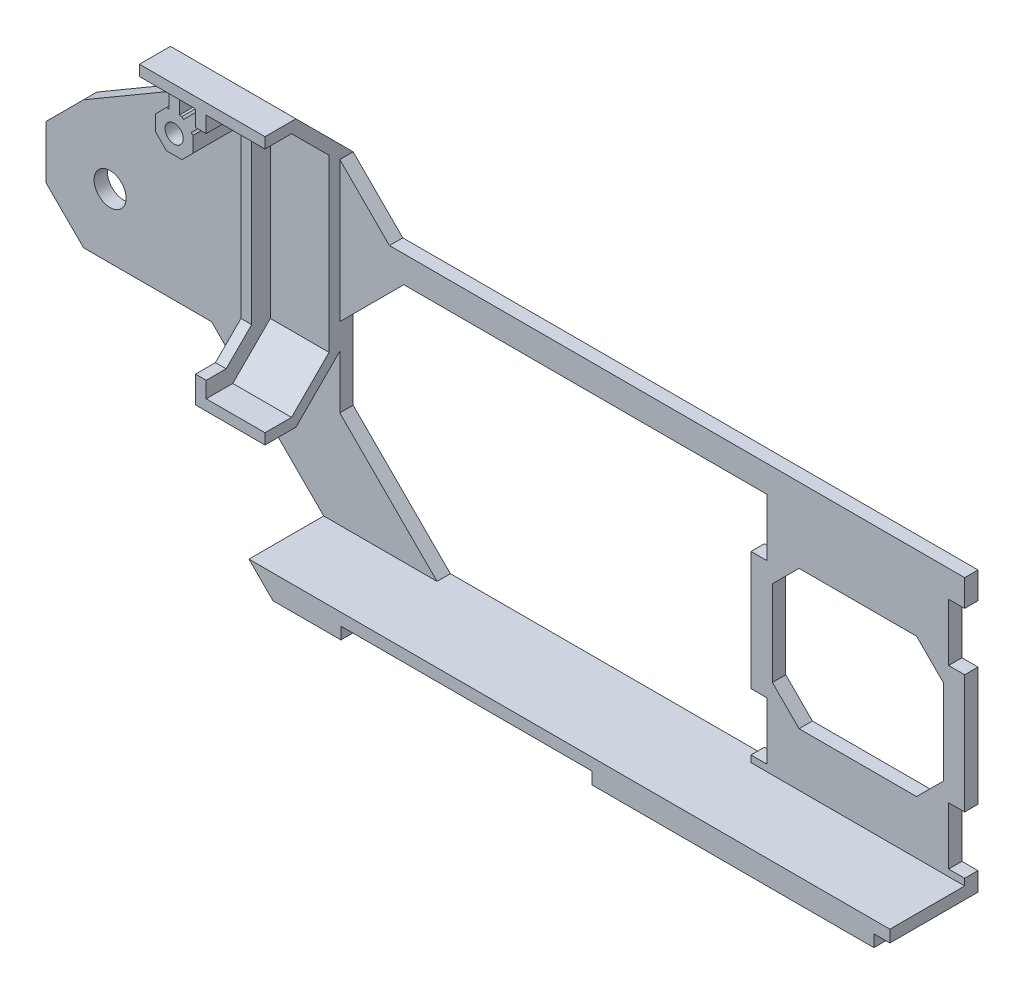
SolidWorks part; units mm, degrees
ref_plane "Front Plane" through (0, 0, 0) normal (0, 0, 1) x (1, 0, 0)
ref_plane "Top Plane" through (0, 0, 0) normal (0, 1, 0) x (1, 0, 0)
ref_plane "Right Plane" through (0, 0, 0) normal (1, 0, 0) x (0, 0, -1)
sketch "Sketch1" plane through (0, 0, 0) normal (0, 0, 1) x (1, 0, 0)
  line L0 (20, 0) -> (-100, 0) construction
  line L1 (0, 33) -> (-140, 33) construction
  line L3 (20, 45) -> (20, -2.25)
  line L5 (-121, 21) -> (-95.5, -4.5)
  line L6 (-17, 45) -> (20, 45) construction
  line L7 (17, -4.5) -> (-95.5, -4.5)
  line L9 (-78.7868, 0) -> (-20, 0)
  line L10 (-20, 0) -> (-20, 34.25)
  line L12 (20, 0) -> (-20, 0) construction
  line L13 (20, -4.5) -> (-100, -4.5) construction
  line L16 (20, -2.25) -> (17, -2.25)
  line L17 (17, -2.25) -> (17, -4.5)
  line L18 (-17, 45) -> (-85, 45)
  line L19 (0, 0) -> (0, 60) construction
  line L22 (16, 45) -> (16, -2.25) construction
  line L23 (0, 33) -> (20, 33) construction
  line L24 (-16, 45) -> (-16, -4.5) construction
  line L25 (20, 45) -> (20, 50)
  line L29 (-144.9706, 45) -> (-139.9706, 50)
  line L34 (20, 50) -> (-97, 50)
  line L41 (-108, 33) -> (-108, 60.9497) construction
  line L42 (11, 36) -> (-11, 36)
  line L43 (-11, 36) -> (-16, 31)
  line L44 (-16, 31) -> (-16, 15)
  line L45 (-16, 15) -> (-11, 10)
  line L46 (-11, 10) -> (11, 10)
  line L47 (11, 10) -> (16, 15)
  line L48 (16, 15) -> (16, 31)
  line L49 (16, 31) -> (11, 36)
  line L50 (-117, 33) -> (-117, 59) construction
  line L52 (-113.5, 57.5503) -> (-113.5, 60.4497)
  line L53 (-113.5, 60.4497) -> (-115.5503, 62.5)
  line L54 (-115.5503, 62.5) -> (-118.4497, 62.5)
  line L55 (-118.4497, 62.5) -> (-120.5, 60.4497)
  line L56 (-120.5, 60.4497) -> (-120.5, 57.5503)
  line L57 (-120.5, 57.5503) -> (-118.4497, 55.5)
  line L58 (-118.4497, 55.5) -> (-115.5503, 55.5)
  line L59 (-115.5503, 55.5) -> (-113.5, 57.5503)
  line L60 (-135.0294, 21) -> (-121, 21)
  line L61 (-135.0294, 45) -> (-144.9706, 45)
  line L62 (-144.9706, 45) -> (-152, 37.9706)
  line L63 (-152, 37.9706) -> (-152, 28.0294)
  line L64 (-152, 28.0294) -> (-144.9706, 21)
  line L65 (-144.9706, 21) -> (-135.0294, 21)
  line L66 (-135.0294, 21) -> (-128, 28.0294)
  line L67 (-128, 28.0294) -> (-128, 37.9706)
  line L68 (-128, 37.9706) -> (-135.0294, 45)
  line L73 (-152, 37.9706) -> (-152, 38.0503)
  line L75 (-97, 33) -> (-97, 50) construction
  line L76 (-78.7868, 0) -> (-97, 18.2132)
  line L78 (-135.0294, 45) -> (-123.7868, 45) construction
  line L79 (-123.7868, 45) -> (-97, 18.2132) construction
  line L81 (-82.7868, 0) -> (-82.7868, -4.5) construction
  line L82 (-35.7868, 0) -> (-35.7868, -4.5) construction
  line L83 (-82.7868, -2.25) -> (-35.7868, -2.25) construction
  line L84 (20, 1.25) -> (17, 1.25)
  line L85 (17, 1.25) -> (17, 12)
  line L86 (17, 12) -> (20, 12)
  line L87 (-20, 12) -> (-17, 12)
  line L88 (-17, 12) -> (-17, 1.25)
  line L89 (-17, 1.25) -> (-20, 1.25)
  line L90 (20, 34.25) -> (17, 34.25)
  line L91 (17, 34.25) -> (17, 45)
  line L92 (17, 45) -> (20, 45)
  line L93 (-20, 34.25) -> (-17, 34.25)
  line L94 (-17, 34.25) -> (-17, 45)
  line L96 (-139.9706, 50) -> (-97, 50)
  line L97 (-97, 50) -> (-97, 59.3)
  line L98 (-97, 59.3) -> (-87.7, 50)
  line L99 (-97, 33) -> (-97, 18.2132)
  line L100 (-97, 33) -> (-85, 45)
  line L102 (-97, 59.3) -> (-113.5, 59.3)
  line L103 (-113.5, 59.3) -> (-120.5, 59.3) construction
  line L104 (-120.5, 59.3) -> (-129.8, 50)
  line L105 (-114.5251, 61.4749) -> (-108.8683, 67.1317) construction
  line L108 (-117, 62.5) -> (-117, 69.5) construction
  line L109 (-116, 62.5) -> (-116, 69.5)
  line L110 (-118, 62.5) -> (-118, 69.5)
  line L111 (-116, 62.5) -> (-118, 62.5)
  line L112 (-116, 69.5) -> (-118, 69.5)
  line L113 (-113.818, 60.7678) -> (-108.1612, 66.4246)
  line L114 (-115.2322, 62.182) -> (-109.5754, 67.8388)
  line L115 (-113.818, 60.7678) -> (-115.2322, 62.182)
  line L116 (-108.1612, 66.4246) -> (-109.5754, 67.8388)
  line L117 (-120.5, 59.3) -> (-144.9706, 45)
  circle A0 centre (-140, 33) radius 3
  circle A2 centre (-117, 59) radius 1.7
  circle A3 centre (-117, 59) radius 3.5 construction
  circle A4 centre (-140, 33) radius 12 construction
  point P30 (0, 0)
  dimension "D5" = 6
  dimension "D6" = 100
  dimension "D12" = 97
  dimension "D14" = 11
  dimension "D15" = 9.3
  dimension "D16" = 45
  dimension "D37" = 3.4
  dimension "D38" = 7
  dimension "D40" = 24
  dimension "D1" = 33
  dimension "D2" = 4.5
  dimension "D3" = 140
  dimension "D4" = 12
  dimension "D7" = 45
  dimension "D8" = 40
  dimension "D9" = 3
  dimension "D10" = 15
  dimension "D11" = 5
  dimension "D13" = 27
  dimension "D17" = 2.25
  dimension "D18" = 135
  dimension "D19" = 8
  dimension "D20" = 4
  dimension "D21" = 4
  dimension "D22" = 1
  dimension "D23" = 7
  dimension "D24" = 1
  dimension "D25" = 1
  dimension "D26" = 1
  dimension "D30" = 3
  dimension "D31" = 10
  dimension "D32" = 135
  dimension "D33" = 135
  dimension "D34" = 5
  dimension "D35" = 23
  dimension "D36" = 26
  dimension "D39" = 4
  dimension "D44" = 47
  dimension "D45" = 3
  dimension "D46" = 1.25
  dimension "D47" = 12
  dimension "D48" = 3
  dimension "D49" = 22.25
sketch "Sketch2" plane through (0, 0, 0) normal (1, 0, 0) x (0, 0, -1)
  line L0 (0, 0) -> (-16.5, 0) construction
  line L1 (0, 45) -> (0, -4.5) construction
  line L2 (0, 0) -> (0, 60) construction
  line L3 (0, 33) -> (-16.5, 33) construction
  line L4 (0, -4.5) -> (-16.5, -4.5) construction
  line L5 (0, 45) -> (-16.5, 45) construction
  line L6 (-16.5, -4.5) -> (-16.5, 59.6517) construction
  line L19 (-2.5, -4.5) -> (-2.5, 45) construction
  line L20 (-11.5294, 33) -> (-2.5, 42.0294) construction
  line L21 (-4, -0.4581) -> (-4, 3.4581) construction
  line L22 (-4, 3.4581) -> (-5.5, 2.1995) construction
  line L23 (-5.5, 2.1995) -> (-5.5, 0.8005) construction
  line L24 (-5.5, 0.8005) -> (-4, -0.4581) construction
  line L25 (-4, 33.6216) -> (-4, 37.5378) construction
  line L26 (-4, 37.5378) -> (-5.5, 36.2792) construction
  line L27 (-5.5, 36.2792) -> (-5.5, 34.8802) construction
  line L28 (-5.5, 34.8802) -> (-4, 33.6216) construction
  line L29 (0, -2.25) -> (-16.5, -2.25) construction
  line L30 (-2.5503, 39.0797) -> (0, 39.0797) construction
  line L31 (-0.5, 2.9497) -> (-2.5503, 5)
  line L32 (-2.5503, 5) -> (-5.4497, 5)
  line L33 (-5.4497, 5) -> (-7.5, 2.9497)
  line L34 (-7.5, 2.9497) -> (-7.5, 0.0503)
  line L35 (-7.5, 0.0503) -> (-5.4497, -2)
  line L36 (-5.4497, -2) -> (-2.5503, -2)
  line L37 (-2.5503, -2) -> (-0.5, 0.0503)
  line L38 (-0.5, 0.0503) -> (-0.5, 2.9497)
  line L39 (-0.5, 37.0294) -> (-2.5503, 39.0797)
  line L40 (-2.5503, 39.0797) -> (-5.4497, 39.0797)
  line L41 (-5.4497, 39.0797) -> (-7.5, 37.0294)
  line L42 (-7.5, 37.0294) -> (-7.5, 34.1299)
  line L43 (-7.5, 34.1299) -> (-5.4497, 32.0797)
  line L44 (-5.4497, 32.0797) -> (-2.5503, 32.0797)
  line L45 (-2.5503, 32.0797) -> (-0.5, 34.1299)
  line L46 (-0.5, 34.1299) -> (-0.5, 37.0294)
  line L47 (0, 32.0797) -> (-2.5503, 32.0797) construction
  line L48 (-2.5503, 5) -> (0, 5) construction
  line L49 (-7.5, -2.25) -> (-7.5, 0.0503) construction
  circle A0 centre (-4, 1.5) radius 1.5
  circle A1 centre (-4, 1.5) radius 3.5 construction
  circle A2 centre (-4, 35.5797) radius 1.5
  circle A3 centre (-4, 35.5797) radius 3.5 construction
  circle A4 centre (-16.5, 45) radius 12 construction
  dimension "D2" = 3
  dimension "D3" = 7
  dimension "D5" = 24
  dimension "D1" = 16.5
  dimension "D4" = 2.5
  dimension "D6" = 45
  dimension "D7" = 50
  dimension "D8" = 50
  dimension "D9" = 2.25
sketch "Sketch4" plane through (0, 0, 0) normal (0, 0, 1) x (1, 0, 0)
  line L0 (-97, 59.3) -> (-113.5, 59.3) construction
  line L1 (-113.5, 59.3) -> (-120.5, 59.3) construction
  line L2 (-121, 21) -> (-95.5, -4.5) construction
  line L3 (17, -4.5) -> (-95.5, -4.5) construction
  line L4 (-82.7868, 0) -> (-82.7868, -4.5) construction
  line L6 (-20, 0) -> (-20, 34.25) construction
  line L7 (-97, 59.3) -> (-113.5, 59.3)
  line L8 (-113.5, 59.3) -> (-120.5, 59.3)
  line L9 (-78.7868, 0) -> (-20, 0) construction
  line L10 (17, -2.25) -> (17, -4.5) construction
  line L11 (20, -2.25) -> (17, -2.25) construction
  line L12 (20, 50) -> (-97, 50) construction
  line L13 (20, 45) -> (20, 50) construction
  line L14 (-135.0294, 21) -> (-121, 21) construction
  line L15 (-121, 21) -> (-95.5, -4.5)
  line L16 (17, -4.5) -> (-35.7868, -4.5)
  line L17 (-78.7868, 0) -> (-97, 18.2132) construction
  line L18 (-17, 45) -> (-85, 45) construction
  line L19 (-20, 0) -> (-20, 1.25)
  line L22 (-78.7868, 0) -> (-20, 0)
  line L23 (17, -2.25) -> (17, -4.5)
  line L24 (20, -2.25) -> (17, -2.25)
  line L29 (-120.5, 59.3) -> (-144.9706, 45) construction
  line L30 (-120.5, 59.3) -> (-144.9706, 45)
  line L31 (20, 50) -> (-87.7, 50)
  line L33 (20, 45) -> (20, 50)
  line L34 (-17, 45) -> (-85, 45)
  line L35 (-97, 33) -> (-85, 45) construction
  line L37 (20, 45) -> (20, -2.25) construction
  line L43 (-144.9706, 45) -> (-152, 37.9706) construction
  line L46 (-144.9706, 45) -> (-152, 37.9706)
  line L47 (-97, 59.3) -> (-87.7, 50) construction
  line L49 (-97, 59.3) -> (-87.7, 50)
  line L50 (11, 36) -> (-11, 36) construction
  line L51 (-11, 36) -> (-16, 31) construction
  line L52 (-16, 31) -> (-16, 15) construction
  line L53 (-16, 15) -> (-11, 10) construction
  line L54 (-11, 10) -> (11, 10) construction
  line L55 (11, 10) -> (16, 15) construction
  line L56 (16, 15) -> (16, 31) construction
  line L57 (16, 31) -> (11, 36) construction
  line L58 (11, 36) -> (-11, 36)
  line L59 (-11, 36) -> (-16, 31)
  line L60 (-16, 31) -> (-16, 15)
  line L61 (-16, 15) -> (-11, 10)
  line L62 (-11, 10) -> (11, 10)
  line L63 (11, 10) -> (16, 15)
  line L64 (16, 15) -> (16, 31)
  line L65 (16, 31) -> (11, 36)
  line L68 (-78.7868, 0) -> (-97, 18.2132)
  line L69 (-82.7868, -2.25) -> (-35.7868, -2.25) construction
  line L70 (-152, 37.9706) -> (-152, 28.0294) construction
  line L71 (-152, 28.0294) -> (-144.9706, 21) construction
  line L72 (-144.9706, 21) -> (-135.0294, 21) construction
  line L75 (-97, 33) -> (-97, 18.2132) construction
  line L76 (-97, 33) -> (-85, 45)
  line L79 (-152, 37.9706) -> (-152, 28.0294)
  line L80 (-152, 28.0294) -> (-144.9706, 21)
  line L81 (-144.9706, 21) -> (-135.0294, 21)
  line L82 (-135.0294, 21) -> (-121, 21)
  line L83 (-97, 33) -> (-97, 18.2132)
  line L86 (-35.7868, 0) -> (-35.7868, -4.5) construction
  line L87 (-82.7868, -2.25) -> (-82.7868, -4.5)
  line L88 (-82.7868, -2.25) -> (-35.7868, -2.25)
  line L89 (-35.7868, -2.25) -> (-35.7868, -4.5)
  line L90 (-82.7868, -4.5) -> (-95.5, -4.5)
  line L91 (17, 12) -> (20, 12) construction
  line L92 (17, 1.25) -> (17, 12) construction
  line L93 (20, 1.25) -> (17, 1.25) construction
  line L94 (17, 12) -> (20, 12)
  line L95 (17, 1.25) -> (17, 12)
  line L96 (20, 1.25) -> (17, 1.25)
  line L98 (-20, 12) -> (-17, 12) construction
  line L99 (-17, 12) -> (-17, 1.25) construction
  line L100 (-17, 1.25) -> (-20, 1.25) construction
  line L101 (-20, 12) -> (-17, 12)
  line L102 (-17, 12) -> (-17, 1.25)
  line L103 (-17, 1.25) -> (-20, 1.25)
  line L104 (-20, 12) -> (-20, 34.25)
  line L108 (17, 34.25) -> (17, 45) construction
  line L109 (20, 34.25) -> (17, 34.25) construction
  line L110 (17, 34.25) -> (17, 45)
  line L111 (20, 34.25) -> (20, 12)
  line L113 (20, 34.25) -> (17, 34.25)
  line L115 (20, 1.25) -> (20, -2.25)
  line L116 (-20, 34.25) -> (-17, 34.25) construction
  line L117 (-17, 34.25) -> (-17, 45) construction
  line L119 (-20, 34.25) -> (-17, 34.25)
  line L120 (-17, 34.25) -> (-17, 45)
  line L124 (17, 45) -> (20, 45)
  circle A1 centre (-140, 33) radius 3 construction
  circle A3 centre (-140, 33) radius 3
extrude "Main Wall" add sketch "Sketch4" along normal up to vertex (2.5 mm away) up to point (0, 45, 2.5)
sketch "Sketch5" plane through (0, 0, 2.5) normal (0, 0, 1) x (1, 0, 0)
  line L0 (20, 45) -> (20, -2.25) construction
  line L1 (20, -2.25) -> (17, -2.25) construction
  line L2 (17, -2.25) -> (17, -4.5) construction
  line L3 (17, -4.5) -> (-95.5, -4.5) construction
  line L4 (-121, 21) -> (-95.5, -4.5) construction
  line L9 (20, 0) -> (20, -2.25)
  line L10 (20, -2.25) -> (17, -2.25)
  line L11 (17, -2.25) -> (17, -4.5)
  line L12 (17, -4.5) -> (-35.7868, -4.5)
  line L13 (-100, 0) -> (-95.5, -4.5)
  line L15 (20, 0) -> (-100, 0) construction
  line L17 (20, 0) -> (-100, 0)
  line L19 (-82.7868, 0) -> (-82.7868, -4.5) construction
  line L20 (-82.7868, -2.25) -> (-35.7868, -2.25) construction
  line L21 (-35.7868, 0) -> (-35.7868, -4.5) construction
  line L22 (-82.7868, -2.25) -> (-82.7868, -4.5)
  line L23 (-82.7868, -2.25) -> (-35.7868, -2.25)
  line L24 (-35.7868, -2.25) -> (-35.7868, -4.5)
  line L25 (-82.7868, -4.5) -> (-95.5, -4.5)
extrude "Base" add sketch "Sketch5" along normal up to vertex (14 mm away) up to point (0, -4.5, 16.5)
ref_plane "Plane1" through (-108, 0, 0) normal (1, 0, 0) x (0, 0, -1)
sketch "Sketch15" plane through (-108, 0, 0) normal (1, 0, 0) x (0, 0, -1)
  line L0 (-16.5, 68) -> (-11.5294, 68) construction
  line L1 (-11.5294, 68) -> (0, 56.4706) construction
  line L3 (-16.5, -4.5) -> (-16.5, 59.6517) construction
  line L4 (0, 30.701) -> (0, 59.299)
  line L5 (-16.5, 56) -> (-16.5, 34) construction
  line L6 (-28.5, 56) -> (-28.5, 34) construction
  line L7 (-16.5, 20) -> (-16.5, 25)
  line L8 (0, 59.299) -> (-10.701, 70)
  line L9 (-8, 60.2279) -> (-8, 29.7721)
  line L10 (-8, 29.7721) -> (-12.7721, 25)
  line L11 (-12.7721, 25) -> (-16.5, 25)
  line L12 (-16.5, 20) -> (-10.701, 20)
  line L13 (-10.701, 20) -> (0, 30.701)
  line L14 (-4.5, 60.9706) -> (-4.5, 29.0294) construction
  line L15 (-16.5, 0) -> (-2.5, 0) construction
  line L16 (-16.5, 22) -> (-11.5294, 22) construction
  line L17 (-11.5294, 22) -> (0, 33.5294) construction
  line L18 (-10.701, 70) -> (-16.5, 70)
  line L19 (-16.5, 70) -> (-16.5, 68)
  line L20 (-16.5, 68) -> (-16.5, 65)
  line L21 (-16.5, 65) -> (-12.7721, 65)
  line L22 (-12.7721, 65) -> (-8, 60.2279)
  circle A1 centre (-16.5, 34) radius 12 construction
  circle A2 centre (-16.5, 56) radius 12 construction
  dimension "D6" = 24
  dimension "D2" = 8
  dimension "D3" = 2
  dimension "D4" = 3
  dimension "D5" = 5.799
  dimension "D7" = 22
  dimension "D8" = 34
  dimension "D9" = 16.5
  dimension "D10" = 135
  dimension "D11" = 3
  dimension "D12" = 135
  dimension "D13" = 2
  dimension "D14" = 2
  dimension "D15" = 3
  dimension "D16" = 3
extrude "Boss-Extrude8" add sketch "Sketch15" against normal blind 2
sketch "Sketch16" plane through (-108, 0, 0) normal (1, 0, 0) x (0, 0, -1)
  line L0 (-16.5, 68) -> (-11.5294, 68) construction
  line L1 (-11.5294, 68) -> (0, 56.4706) construction
  line L2 (-4.5, 60.9706) -> (-4.5, 29.0294) construction
  line L3 (-11.5294, 22) -> (0, 33.5294) construction
  line L4 (-16.5, 22) -> (-11.5294, 22) construction
  line L5 (-16.5, 20) -> (-16.5, 25) construction
  line L6 (-16.5, 20) -> (-10.701, 20) construction
  line L7 (-10.701, 20) -> (0, 30.701) construction
  line L8 (0, 30.701) -> (0, 59.299) construction
  line L9 (0, 59.299) -> (-10.701, 70) construction
  line L10 (-10.701, 70) -> (-16.5, 70) construction
  line L11 (-16.5, 70) -> (-16.5, 68) construction
  line L12 (-16.5, 68) -> (-11.5294, 68)
  line L13 (-11.5294, 68) -> (-4.5, 60.9706)
  line L14 (-4.5, 60.9706) -> (-4.5, 29.0294)
  line L15 (-11.5294, 22) -> (-4.5, 29.0294)
  line L16 (-16.5, 22) -> (-11.5294, 22)
  line L17 (-16.5, 20) -> (-16.5, 22)
  line L18 (-16.5, 20) -> (-10.701, 20)
  line L19 (-10.701, 20) -> (0, 30.701)
  line L20 (0, 30.701) -> (0, 59.299)
  line L21 (0, 59.299) -> (-10.701, 70)
  line L22 (-10.701, 70) -> (-16.5, 70)
  line L23 (-16.5, 70) -> (-16.5, 68)
extrude "Boss-Extrude9" add sketch "Sketch16" along normal blind 11
sketch "Sketch17" plane through (-108, 0, 0) normal (1, 0, 0) x (0, 0, -1)
  line L0 (0, 59.299) -> (-10.701, 70) construction
  line L1 (-10.701, 70) -> (-16.5, 70) construction
  line L2 (-16.5, 70) -> (-16.5, 68) construction
  line L3 (-16.5, 68) -> (-11.5294, 68) construction
  line L4 (-11.5294, 68) -> (0, 56.4706) construction
  line L5 (0, 30.701) -> (0, 59.299) construction
  line L6 (-2.5, 59.3) -> (-2.5, 33) construction
  line L7 (0, 59.299) -> (-10.701, 70)
  line L8 (-10.701, 70) -> (-16.5, 70)
  line L9 (-16.5, 70) -> (-16.5, 68)
  line L10 (-16.5, 68) -> (-11.5294, 68)
  line L11 (-11.5294, 68) -> (-2.5, 58.9706)
  line L12 (0, 50) -> (0, 59.299)
  line L13 (-2.5, 58.9706) -> (-2.5, 50)
  line L14 (-2.5, 50) -> (0, 50) construction
  line L15 (-2.5, 50) -> (0, 50)
ref_plane "Plane2" through (0, 0, 13.5) normal (0, 0, 1) x (1, 0, 0)
extrude "Boss-Extrude15" add sketch "Sketch17" against normal up to vertex (12.5 mm away) up to point (-120.5, 57.5503, 0)
sketch "Sketch18" plane through (0, 0, 13.5) normal (0, 0, 1) x (1, 0, 0)
  line L0 (-115.5503, 62.5) -> (-118.4497, 62.5) construction
  line L1 (-118.4497, 62.5) -> (-120.5, 60.4497) construction
  line L2 (-120.5, 60.4497) -> (-120.5, 57.5503) construction
  line L3 (-120.5, 57.5503) -> (-118.4497, 55.5) construction
  line L4 (-118.4497, 55.5) -> (-115.5503, 55.5) construction
  line L5 (-115.5503, 55.5) -> (-113.5, 57.5503) construction
  line L7 (-113.5, 60.4497) -> (-115.5503, 62.5) construction
  line L8 (-115.5503, 62.5) -> (-116, 62.5)
  line L9 (-118.4497, 62.5) -> (-120.5, 60.4497)
  line L10 (-120.5, 60.4497) -> (-120.5, 57.5503)
  line L11 (-120.5, 57.5503) -> (-118.4497, 55.5)
  line L12 (-118.4497, 55.5) -> (-115.5503, 55.5)
  line L13 (-115.5503, 55.5) -> (-113.5, 57.5503)
  line L14 (-113.5, 57.5503) -> (-113.5, 60.4497) construction
  line L15 (-113.5, 60.4497) -> (-113.818, 60.7678)
  line L16 (-118, 62.5) -> (-118, 69.5) construction
  line L17 (-116, 62.5) -> (-116, 69.5) construction
  line L18 (-116, 69.5) -> (-118, 69.5) construction
  line L22 (-118, 62.5) -> (-118, 69.5)
  line L23 (-116, 62.5) -> (-116, 69.5)
  line L24 (-116, 69.5) -> (-118, 69.5)
  line L25 (-113.818, 60.7678) -> (-108.1612, 66.4246) construction
  line L26 (-115.2322, 62.182) -> (-109.5754, 67.8388) construction
  line L27 (-108.1612, 66.4246) -> (-109.5754, 67.8388) construction
  line L28 (-118, 62.5) -> (-118.4497, 62.5)
  line L29 (-113.5, 57.5503) -> (-113.5, 60.4497)
  line L30 (-113.818, 60.7678) -> (-108.1612, 66.4246)
  line L31 (-115.2322, 62.182) -> (-109.5754, 67.8388)
  line L32 (-108.1612, 66.4246) -> (-109.5754, 67.8388)
  line L33 (-115.2322, 62.182) -> (-115.5503, 62.5)
extrude "Boss-Extrude13" add sketch "Sketch18" against normal up to next
sketch "Sketch19" plane through (0, 0, 13.5) normal (0, 0, 1) x (1, 0, 0)
  circle A0 centre (-117, 59) radius 1.7 construction
  circle A1 centre (-117, 59) radius 1.7
extrude "Cut-Extrude1" cut sketch "Sketch19" against normal blind 7
